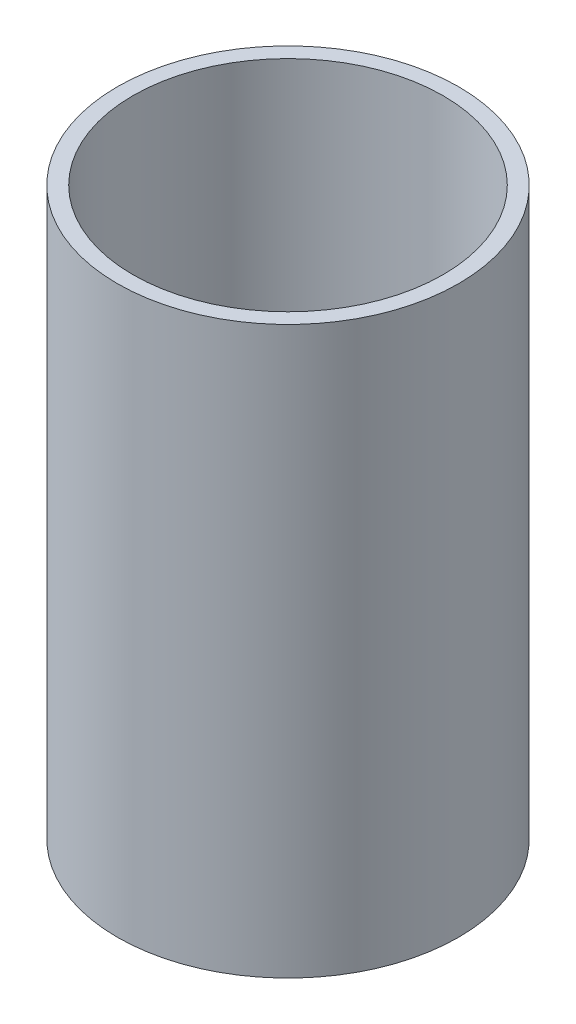
SolidWorks part; units mm, degrees
ref_plane "Front Plane" through (0, 0, 0) normal (0, 0, 1) x (1, 0, 0)
ref_plane "Top Plane" through (0, 0, 0) normal (0, 1, 0) x (1, 0, 0)
ref_plane "Right Plane" through (0, 0, 0) normal (1, 0, 0) x (0, 0, -1)
sketch "Sketch1" plane through (0, 0, 0) normal (0, 1, 0) x (1, 0, 0)
  circle A0 centre (0, 0) radius 20
  circle A1 centre (0, 0) radius 22
  dimension "D1" = 40
  dimension "D2" = 44
extrude "Boss-Extrude1" add sketch "Sketch1" along normal blind 73
